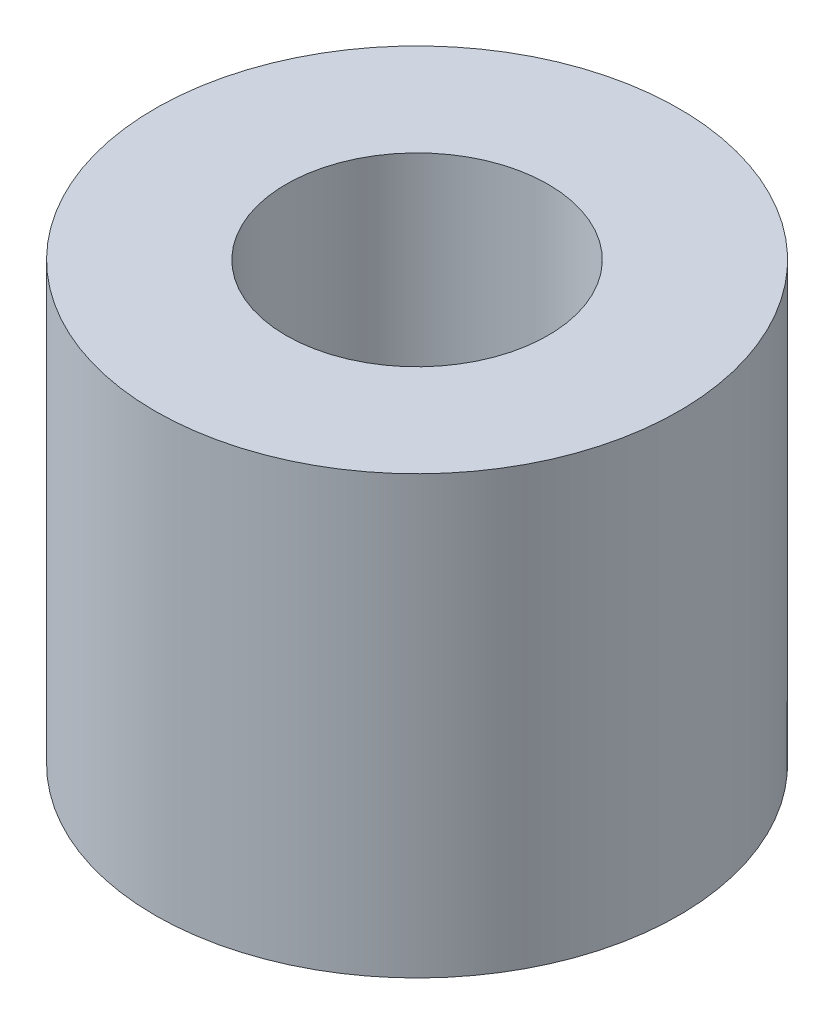
SolidWorks part; units mm, degrees
ref_plane "Front Plane" through (0, 0, 0) normal (0, 0, 1) x (1, 0, 0)
ref_plane "Top Plane" through (0, 0, 0) normal (0, 1, 0) x (1, 0, 0)
ref_plane "Right Plane" through (0, 0, 0) normal (1, 0, 0) x (0, 0, -1)
sketch "Sketch1" plane through (0, 0, 0) normal (0, 1, 0) x (1, 0, 0)
  circle A0 centre (0, 0) radius 1.5
  circle A1 centre (0, 0) radius 3
  dimension "D1" = 3
  dimension "D2" = 6
extrude "Boss-Extrude1" add sketch "Sketch1" along normal blind 5
